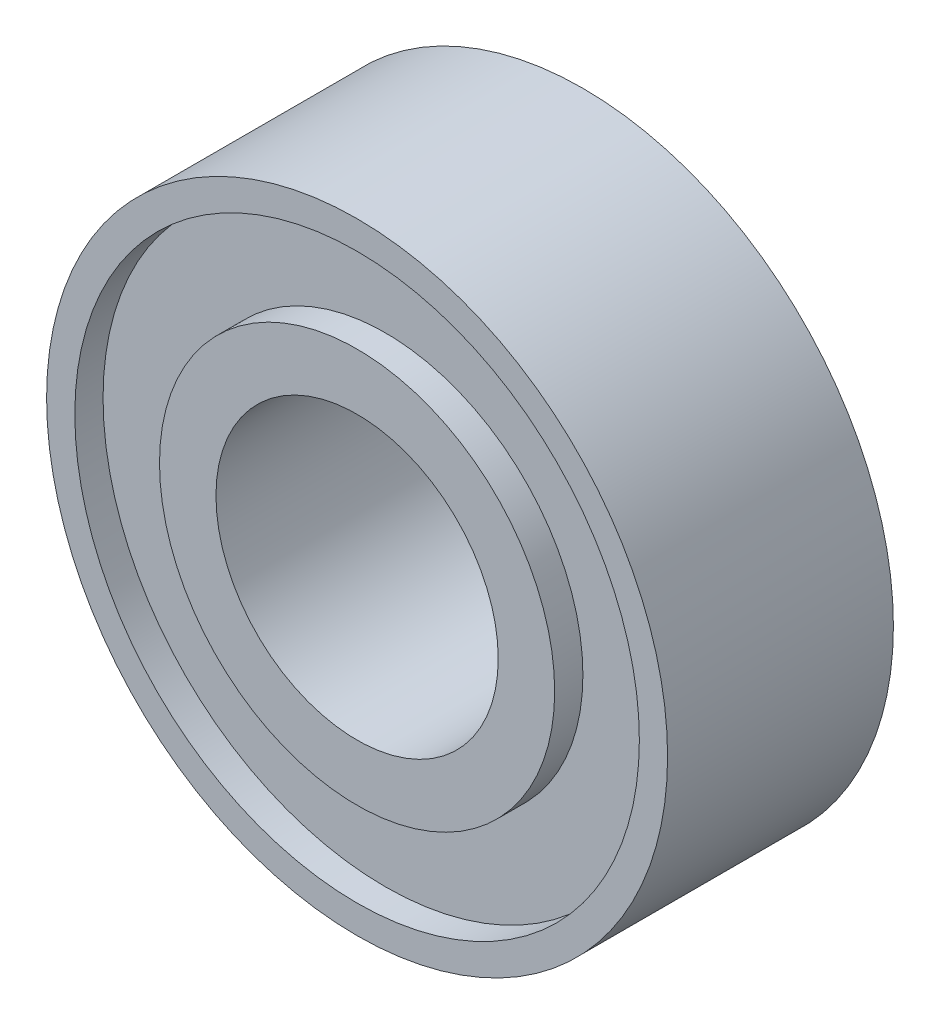
SolidWorks part; units mm, degrees
ref_plane "Front Plane" through (0, 0, 0) normal (0, 0, 1) x (1, 0, 0)
ref_plane "Top Plane" through (0, 0, 0) normal (0, 1, 0) x (1, 0, 0)
ref_plane "Right Plane" through (0, 0, 0) normal (1, 0, 0) x (0, 0, -1)
sketch "Sketch2" plane through (0, 0, 0) normal (0, 0, 1) x (1, 0, 0)
  circle A0 centre (5.7264, 6.633) radius 5.5
  circle A1 centre (5.7264, 6.633) radius 2.5
  dimension "D1" = 11
  dimension "D2" = 5
extrude "Boss-Extrude1" add sketch "Sketch2" along normal blind 2 contours A0
sketch "Sketch4" plane through (0, 0, 2) normal (0, 0, 1) x (1, 0, 0)
  circle A0 centre (5.7264, 6.633) radius 3.5
  circle A1 centre (5.7264, 6.633) radius 5
  circle A2 centre (5.7264, 6.633) radius 2.5 construction
  dimension "D1" = 1
  dimension "D2" = 10
extrude "Cut-Extrude1" cut sketch "Sketch4" against normal blind 0.5 contours A1
mirror "Mirror2" about plane through (5.7264, 6.633, 0) normal (0, 0, 1) of "Cut-Extrude1", "Boss-Extrude1"
